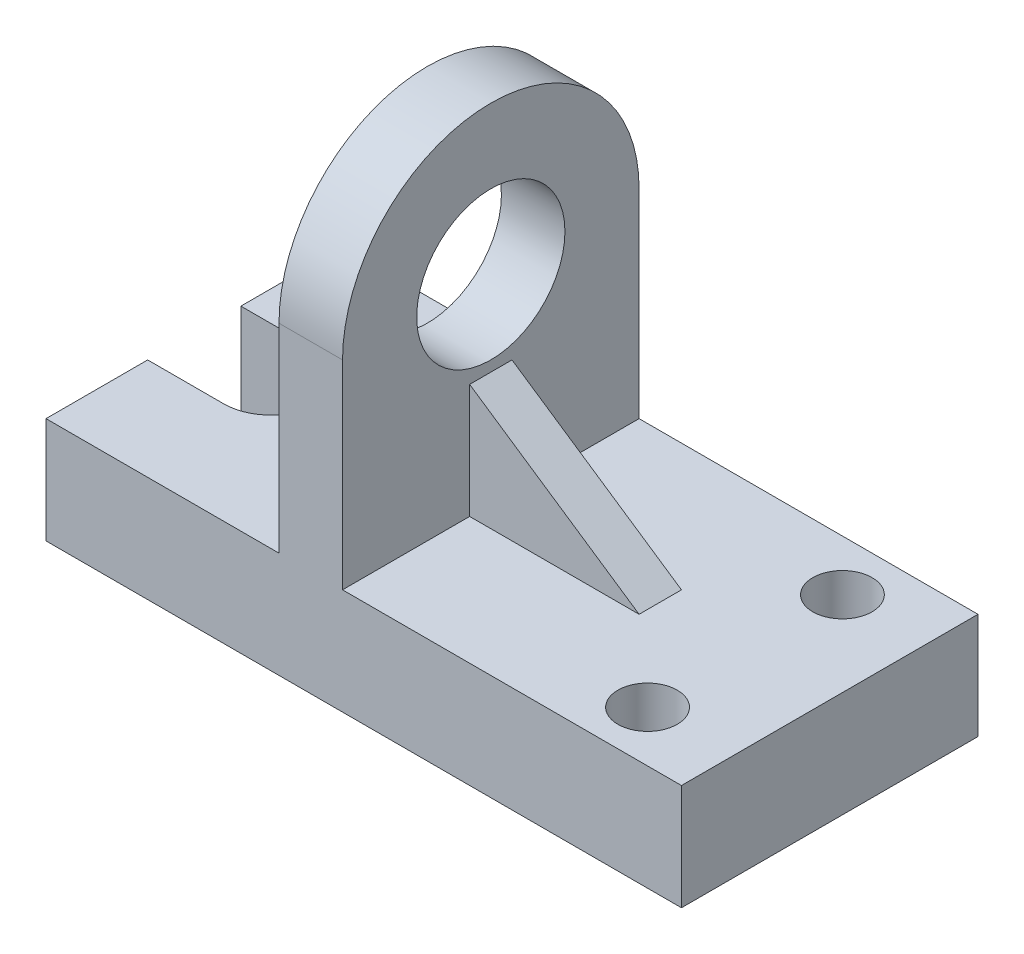
SolidWorks part; units mm, degrees
ref_plane "Спереди" through (0, 0, 0) normal (0, 0, 1) x (1, 0, 0)
ref_plane "Сверху" through (0, 0, 0) normal (0, 1, 0) x (1, 0, 0)
ref_plane "Справа" through (0, 0, 0) normal (1, 0, 0) x (0, 0, -1)
sketch "Эскиз1" plane through (0, 0, 0) normal (0, 0, 1) x (1, 0, 0)
  line L1 (0, 0) -> (150, 0)
  line L2 (0, 0) -> (0, -25)
  line L3 (0, -25) -> (150, -25)
  line L4 (150, 0) -> (150, -25)
  point P4 (0, 0)
  point P5 (0, 0)
  point P7 (0, 0)
  dimension "D1" = 150
  dimension "D2" = 25
extrude "Бобышка-Вытянуть1" add sketch "Эскиз1" along normal blind 70
sketch "Эскиз2" plane through (0, 0, 0) normal (0, 1, 0) x (1, 0, 0)
  line L0 (150, -35) -> (0, -35) construction
  line L1 (150, -70) -> (150, 0) construction
  line L2 (0, -70) -> (0, 0) construction
  line L3 (0, -24) -> (18, -24)
  line L4 (18, -46) -> (0, -46)
  line L5 (130, 0) -> (130, -70) construction
  line L6 (150, 0) -> (0, 0) construction
  line L7 (150, -70) -> (0, -70) construction
  arc A0 (18, -24) -> (18, -46) centre (18, -35) cw
  circle A1 centre (130, -12) radius 7
  circle A2 centre (130, -58) radius 7
  point P22 (0, 0)
  point P23 (0, 0)
  point P25 (0, 0)
  point P26 (0, 0)
  line M6 (0, 0) -> (0, -70)
  dimension "D1" = 22
  dimension "D2" = 18
  dimension "D3" = 12
  dimension "D4" = 14
  dimension "D5" = 20
extrude "Вырез-Вытянуть1" cut sketch "Эскиз2" against normal through all contours A0 L3 L4 M6 | A1 | A2
sketch "Эскиз3" plane through (150, 0, 0) normal (1, 0, 0) x (0, 0, -1)
  line L0 (-70, 0) -> (-70, 47)
  line L1 (0, 47) -> (0, 0)
  line L2 (0, 0) -> (-70, 0)
  line L3 (-35, 0) -> (-35, 82) construction
  line L4 (-70, 47) -> (0, 47) construction
  arc A0 (-70, 47) -> (0, 47) centre (-35, 47) cw
  circle A1 centre (-35, 47) radius 17.5
  point P10 (0, 0)
  dimension "D1" = 35
  dimension "D2" = 47
extrude "Бобышка-Вытянуть2" add sketch "Эскиз3" against normal blind 15 from offset 80 offset against normal yes
sketch3d "Трехмерный эскиз1"
  line L0 (70, 0, 35) -> (150, 0, 35) construction
  line L1 (70, 0, 70) -> (70, 0, 0) construction
  line L2 (150, 0, 70) -> (150, 0, 0) construction
  line L3 (70, 0, 35) -> (70, 29.5, 35) construction
  line L4 (70, 27, 35) -> (110, 0, 35)
  line L5 (110, 0, 35) -> (70, 0, 35)
  line L6 (70, 27, 35) -> (70, 0, 35)
  circle A0 centre (70, 47, 35) radius 17.5 construction
  point P9 (87.5, 47, 35)
  dimension "D1" = 40
  dimension "D2" = 27
extrude "Бобышка-Вытянуть5" add sketch "Трехмерный эскиз1" along direction (0, 0, 1) on the side of the normal blind 5 and the other way blind 5 contours L5 L6 L4
